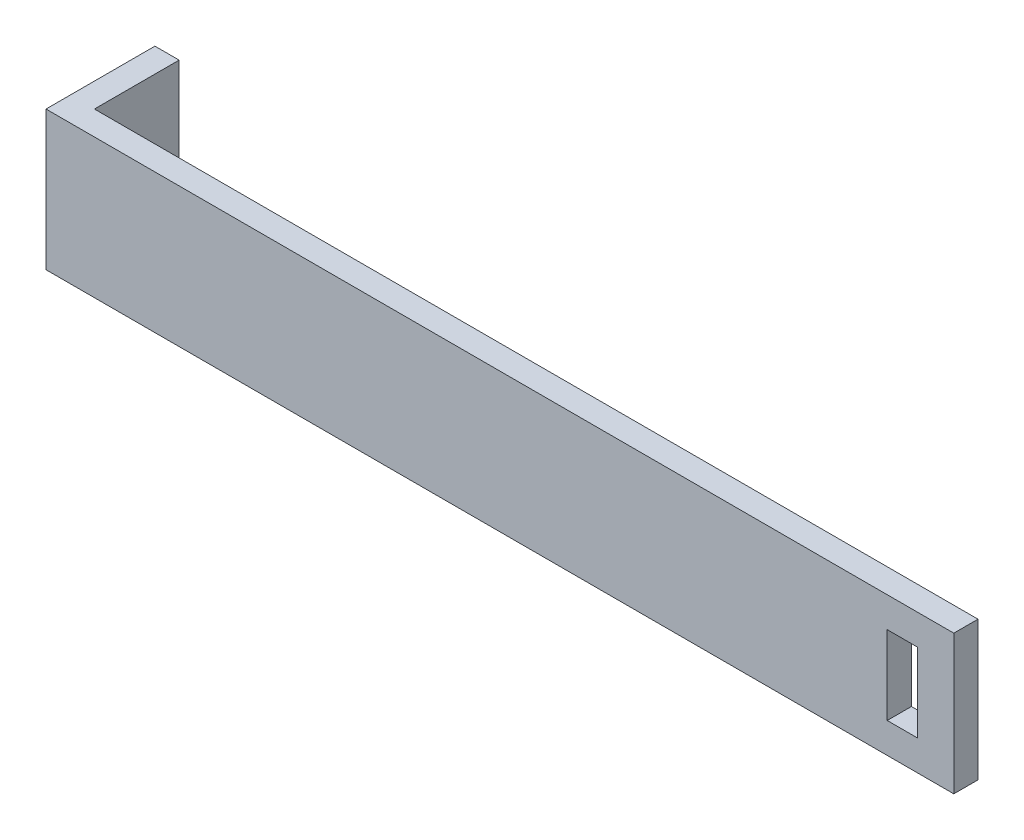
SolidWorks part; units mm, degrees
ref_plane "Front Plane" through (0, 0, 0) normal (0, 0, 1) x (1, 0, 0)
ref_plane "Top Plane" through (0, 0, 0) normal (0, 1, 0) x (1, 0, 0)
ref_plane "Right Plane" through (0, 0, 0) normal (1, 0, 0) x (0, 0, -1)
other "Graphic1"
sketch "Sketch2" plane through (0, 0, 0) normal (0, 0, 1) x (1, 0, 0)
  line L2 (-89.8268, 45.9957) -> (-14.8268, 45.9957)
  line L3 (-89.8268, 45.9957) -> (-89.8268, 34.4957)
  line L4 (-89.8268, 34.4957) -> (-14.8268, 34.4957)
  line L5 (-14.8268, 45.9957) -> (-14.8268, 34.4957)
  dimension "D1" = 75
  dimension "D2" = 11.5
extrude "Boss-Extrude1" add sketch "Sketch2" along normal blind 2
sketch "Sketch3" plane through (0, 0, 0) normal (0, 0, -1) x (-1, 0, 0)
  line L0 (89.8268, 34.4957) -> (14.8268, 34.4957) construction
  line L1 (89.8268, 45.9957) -> (87.8268, 45.9957)
  line L2 (89.8268, 45.9957) -> (89.8268, 34.4957)
  line L3 (89.8268, 34.4957) -> (87.8268, 34.4957)
  line L4 (87.8268, 45.9957) -> (87.8268, 34.4957)
  dimension "D1" = 2
extrude "Boss-Extrude2" add sketch "Sketch3" along normal blind 7
sketch "Sketch4" plane through (0, 0, 2) normal (0, 0, 1) x (1, 0, 0)
  line L0 (-14.8268, 34.4957) -> (-14.8268, 45.9957) construction
  line L1 (-20.3268, 43.4957) -> (-17.8268, 43.4957)
  line L2 (-20.3268, 43.4957) -> (-20.3268, 36.9957)
  line L3 (-20.3268, 36.9957) -> (-17.8268, 36.9957)
  line L4 (-17.8268, 43.4957) -> (-17.8268, 36.9957)
  line L6 (-89.8268, 34.4957) -> (-14.8268, 34.4957) construction
  dimension "D1" = 2.5
  dimension "D2" = 3
  dimension "D3" = 6.5
  dimension "D4" = 2.5
extrude "Cut-Extrude1" cut sketch "Sketch4" against normal blind 10
